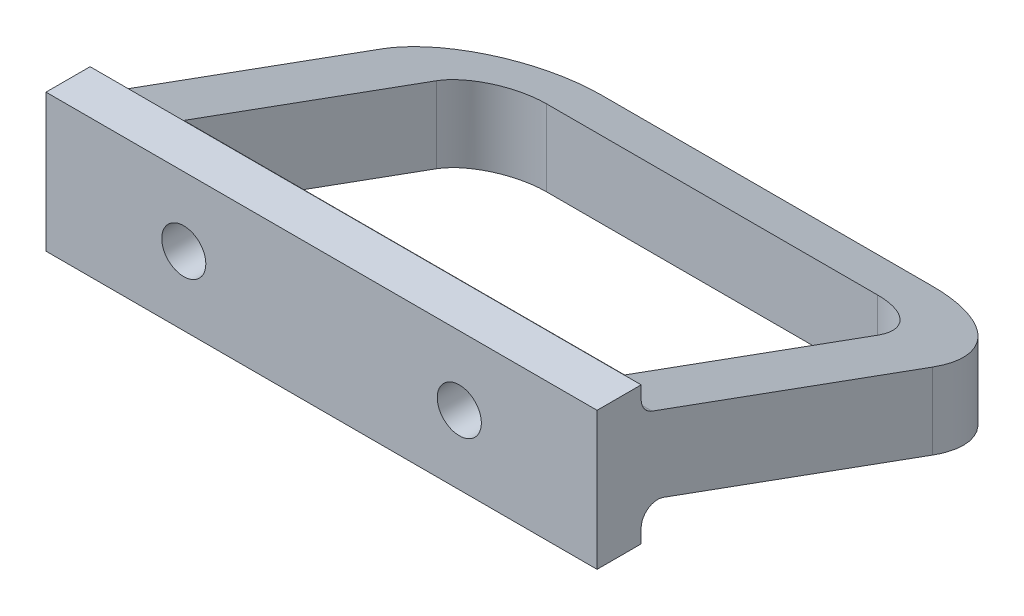
SolidWorks part; units mm, degrees
ref_plane "Front Plane" through (0, 0, 0) normal (1, 0, 0) x (0, 1, 0)
ref_plane "Top Plane" through (0, 0, 0) normal (0, 0, 1) x (0, 1, 0)
ref_plane "Right Plane" through (0, 0, 0) normal (0, 1, 0) x (-1, 0, 0)
sketch "Sketch1" plane through (0, 0, 0) normal (1, 0, 0) x (0, 1, 0)
  line L0 (-12.5, 0) -> (-12.5, -8)
  line L1 (-12.5, -8) -> (-10.0191, -8)
  line L2 (-7.2, -12.0261) -> (-32.25, -80.8504)
  line L3 (-32.25, -80.8504) -> (-18.4157, -80.8504)
  line L4 (-18.4157, -80.8504) -> (7.3812, -9.9739)
  line L5 (10.2003, -8) -> (12.5, -8)
  line L6 (12.5, -8) -> (12.5, 0)
  line L7 (12.5, 0) -> (-12.5, 0)
  line L8 (12.5, -8) -> (12.5, -62.866) construction
  arc A0 (7.3812, -9.9739) -> (10.2003, -8) centre (10.2003, -11) cw
  arc A1 (-10.0191, -8) -> (-7.2, -12.0261) centre (-10.0191, -11) cw
  point P2 (0, 0)
  point P16 (-5.7346, -8)
  dimension "D7" = 3
  dimension "D1" = 8
  dimension "D2" = 13
  dimension "D3" = 20
  dimension "D4" = 25
  dimension "D5" = 44.75
  dimension "D6" = 19.7
extrude "Boss-Extrude1" add sketch "Sketch1" against normal blind 100
sketch "Sketch5" plane through (0, 12.5, 0) normal (0, 1, 0) x (-1, 0, 0)
  line L0 (10, -15) -> (10, -60.8504)
  line L1 (20, -70.8504) -> (80, -70.8504)
  line L2 (90, -60.8504) -> (90, -15)
  line L3 (90, -15) -> (10, -15)
  line L4 (100, 0) -> (0, 0) construction
  line L5 (0, -80.8504) -> (0, -9.9739) construction
  line L6 (100, -80.8504) -> (100, -9.9739) construction
  line L7 (100, -80.8504) -> (0, -80.8504) construction
  arc A0 (80, -70.8504) -> (90, -60.8504) centre (80, -60.8504) ccw
  arc A1 (10, -60.8504) -> (20, -70.8504) centre (20, -60.8504) ccw
  dimension "D5" = 10
  dimension "D1" = 15
  dimension "D2" = 10
  dimension "D3" = 10
  dimension "D4" = 10
extrude "Cut-Extrude3" cut sketch "Sketch5" against normal up to surface (37.4706 mm away)
fillet "Fillet2" radius 20 2 edges at (-100, -25.3328, -80.8504) (0, -25.3328, -80.8504)
sketch "Sketch6" plane through (0, 0, 0) normal (0, 0, 1) x (1, 0, 0)
  line L0 (-100, 12.5) -> (0, 12.5) construction
  circle A0 centre (-75, 0) radius 4
  circle A1 centre (-25, 0) radius 4
  point P4 (0, 0)
  dimension "D1" = 8
  dimension "D2" = 50
  dimension "D3" = 25
  dimension "D4" = 12.5
extrude "Cut-Extrude4" cut sketch "Sketch6" against normal up to surface (15 mm away) up to face at (-50, -1.3653, -15)
